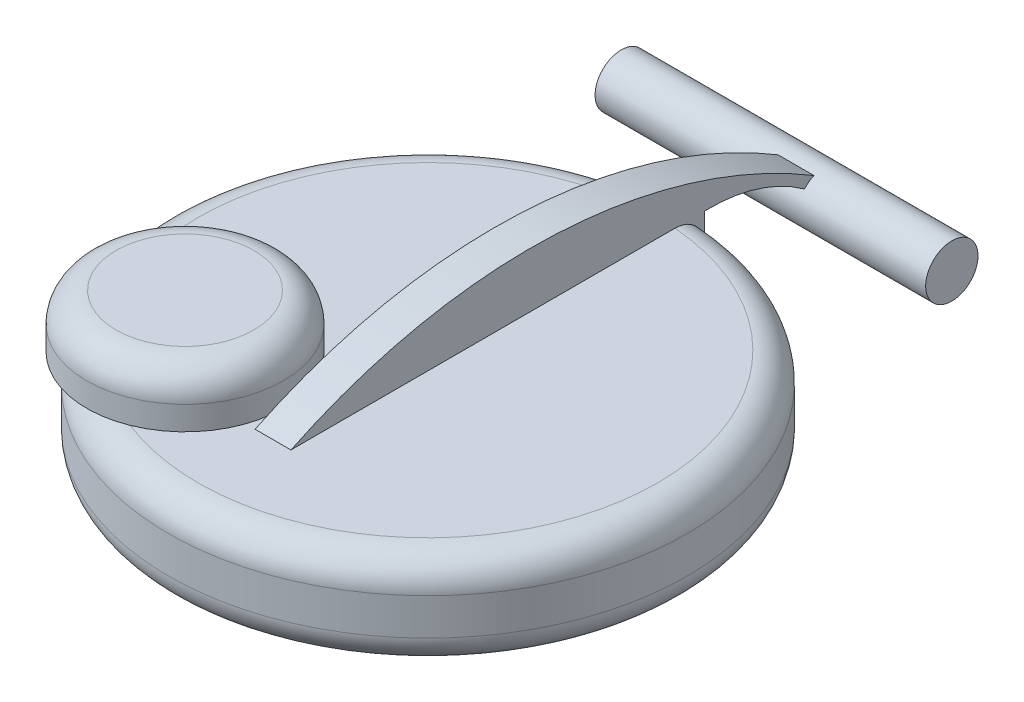
SolidWorks part; units mm, degrees
material "6061 Alloy"
ref_plane "Front Plane" through (0, 0, 0) normal (0, 0, 1) x (1, 0, 0)
ref_plane "Top Plane" through (0, 0, 0) normal (0, 1, 0) x (1, 0, 0)
ref_plane "Right Plane" through (0, 0, 0) normal (1, 0, 0) x (0, 0, -1)
sketch "Sketch1" plane through (0, 0, 0) normal (1, 0, 0) x (0, 0, -1)
  circle A0 centre (0, 0) radius 2.2606
  dimension "D1" = 4.5212
extrude "Boss-Extrude1" add sketch "Sketch1" along normal blind 28.575
ref_plane "Plane1" through (17.5514, 0, 0) normal (1, 0, 0) x (0, 0, -1)
sketch "Sketch2" plane through (17.5514, 0, 0) normal (1, 0, 0) x (0, 0, -1)
  line L0 (-46.101, 4.1402) -> (-10.3124, 4.1402)
  line L1 (15.7163, 0) -> (-15.7163, 0) construction
  line L2 (0, 6.1351) -> (0, -6.1351) construction
  line L3 (0, 0) -> (2.2606, 0)
  arc A0 (-10.3124, 4.1402) -> (0, 0) centre (-9.9209, -9.7978) cw
  arc A1 (-46.101, 4.1402) -> (2.2606, 0) centre (-25.3985, -38.5602) cw
  circle A2 centre (0, 0) radius 2.2606 construction
  dimension "D4" = 47.4544
  dimension "D5" = 13.9435
  dimension "D1" = 35.7886
  dimension "D2" = 4.1402
  dimension "D3" = 10.3124
extrude "Boss-Extrude2" add sketch "Sketch2" against normal blind 3.0988
sketch "Sketch3" plane through (0, 4.1402, 0) normal (0, -1, 0) x (1, 0, 0)
  line L0 (16.002, 46.101) -> (16.002, 10.3124) construction
  line L1 (14.4526, 46.101) -> (17.5514, 46.101) construction
  line L2 (14.4526, 10.3124) -> (17.5514, 10.3124) construction
  circle A0 centre (16.002, 32.7152) radius 22.4028
  dimension "D1" = 44.8056
extrude "Boss-Extrude3" add sketch "Sketch3" along normal blind 8.255
fillet "Fillet1" radius 2.54 2 edges at (16.002, -4.1148, 10.3124) (16.002, 4.1402, 55.118)
sketch "Sketch4" plane through (0, 4.1402, 0) normal (0, 1, 0) x (1, 0, 0)
  circle A0 centre (5.6149, -43.3187) radius 8.4963
  point P2 (5.6149, -43.3187)
  dimension "D1" = 16.9926
extrude "Boss-Extrude4" add sketch "Sketch4" along normal blind 4.5974
fillet "Fillet2" radius 2.54 1 edges at (5.6149, 8.7376, 51.815)
